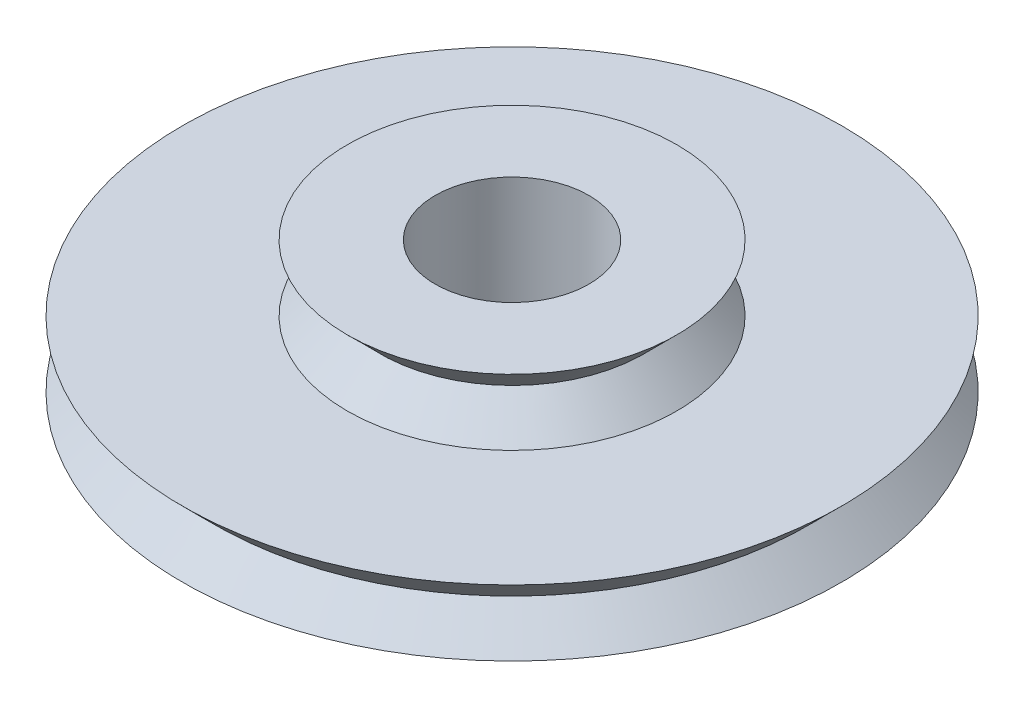
SolidWorks part; units mm, degrees
ref_plane "Front Plane" through (0, 0, 0) normal (0, 0, 1) x (1, 0, 0)
ref_plane "Top Plane" through (0, 0, 0) normal (0, 1, 0) x (1, 0, 0)
ref_plane "Right Plane" through (0, 0, 0) normal (1, 0, 0) x (0, 0, -1)
sketch "Sketch1" plane through (0, 0, 0) normal (0, 0, 1) x (1, 0, 0)
  line L0 (0, 0) -> (0, 13.2622) construction
  line L1 (-3.5, 6) -> (-3.5, 0)
  line L2 (-3.5, 0) -> (-15, 0)
  line L3 (-15, 0) -> (-13.5, 1.5)
  line L4 (-13.5, 1.5) -> (-15, 3)
  line L5 (-15, 3) -> (-7.5, 3)
  line L6 (-7.5, 3) -> (-6, 4.5)
  line L7 (-6, 4.5) -> (-7.5, 6)
  line L8 (-7.5, 6) -> (-3.5, 6)
  point P3 (0, 0)
  dimension "D1" = 3
  dimension "D2" = 7
  dimension "D3" = 15
  dimension "D4" = 30
  dimension "D5" = 45
revolve "Revolve1" add sketch "Sketch1" angle 360 about L0
